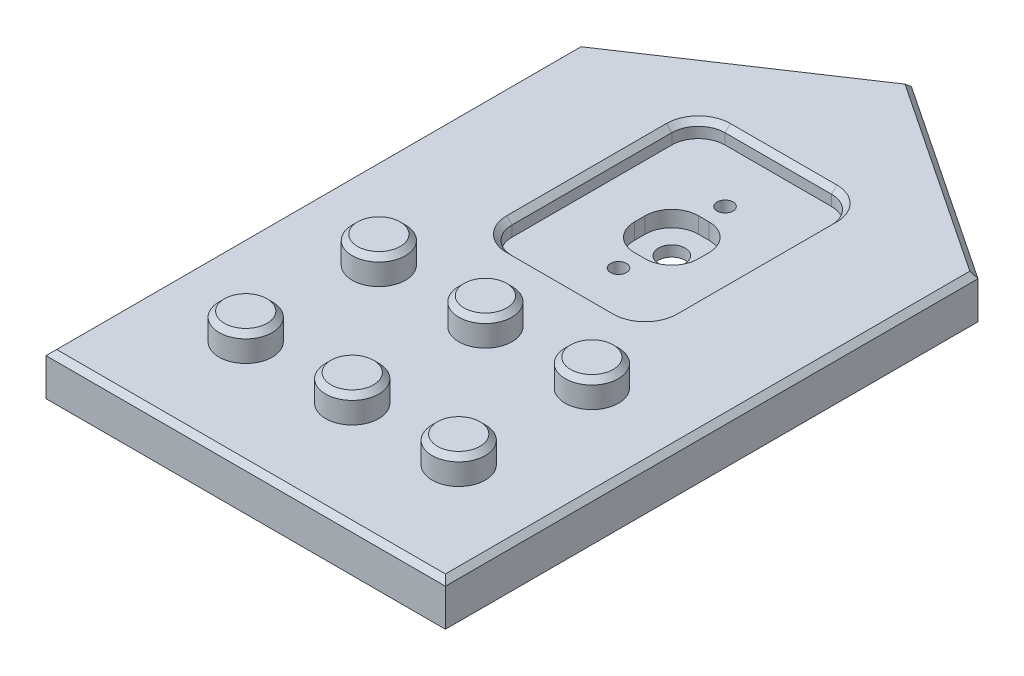
SolidWorks part; units mm, degrees
ref_plane "Front Plane" through (0, 0, 0) normal (0, 0, 1) x (1, 0, 0)
ref_plane "Top Plane" through (0, 0, 0) normal (0, 1, 0) x (1, 0, 0)
ref_plane "Right Plane" through (0, 0, 0) normal (1, 0, 0) x (0, 0, -1)
sketch "Sketch1" plane through (0, 0, 0) normal (0, 1, 0) x (1, 0, 0)
  line L0 (-37.5, 0) -> (37.5, 0)
  line L5 (37.5, 0) -> (37.5, 100)
  line L6 (37.5, 100) -> (-37.5, 100)
  line L7 (-37.5, 100) -> (-37.5, 0)
  line L8 (-37.5, 100) -> (0, 125)
  line L9 (0, 125) -> (37.5, 100)
  line L10 (0, 125) -> (0, 100) construction
  dimension "D1" = 100
  dimension "D2" = 75
  dimension "D3" = 25
extrude "Boss-Extrude1" add sketch "Sketch1" along normal blind 8
sketch "Sketch2" plane through (0, 0, 0) normal (1, 0, 0) x (0, 0, -1)
  line L0 (20, 8) -> (20, 34.3258) construction
  line L1 (0, 8) -> (100, 8) construction
  line L2 (15, 8) -> (23.3313, 8) construction
  line L3 (15, 8) -> (23.3313, 8)
  line L4 (0, 8) -> (0, 0) construction
  line L5 (20, 13) -> (20, 8)
  line L6 (20, 8) -> (15, 8)
  line L7 (15, 8) -> (15, 13)
  line L8 (15, 13) -> (20, 13)
  dimension "D2" = 20
revolve "Revolve1" add sketch "Sketch2" angle 360 about L0
pattern_linear "LPattern1" count 2 spacing 20 along (-1, 0, 0) count 2 spacing 20 along (1, 0, 0) of "Revolve1"
pattern_linear "LPattern2" count 2 spacing 25 along (0, 0, -1) of "LPattern1", "Revolve1"
sketch "Sketch3" plane through (0, 8, 0) normal (0, 1, 0) x (1, 0, 0)
  line L0 (0, 0) -> (0, 125) construction
  line L1 (-37.5, 0) -> (37.5, 0) construction
  line L3 (-15, 100) -> (15, 100)
  line L4 (-15, 100) -> (-15, 60)
  line L5 (-15, 60) -> (15, 60)
  line L6 (15, 100) -> (15, 60)
  point P9 (0, 60)
  point P10 (0, 0)
  dimension "D1" = 30
  dimension "D2" = 40
  dimension "D3" = 25
extrude "Cut-Extrude1" cut sketch "Sketch3" against normal blind 3
fillet "Fillet1" radius 5 4 edges at (15, 6.5, -60) (15, 6.5, -100) (-15, 6.5, -60) (-15, 6.5, -100)
sketch "Sketch4" plane through (0, 5, 0) normal (0, 1, 0) x (1, 0, 0)
  line L0 (0, 100) -> (0, 60) construction
  line L1 (10, 100) -> (-10, 100) construction
  line L2 (-10, 60) -> (10, 60) construction
  circle A0 centre (0, 90) radius 1.5
  circle A1 centre (0, 80) radius 2.5
  circle A2 centre (0, 70) radius 1.5
  point P6 (0, 90)
  point P7 (0, 80)
  point P8 (0, 70)
  dimension "D4" = 3
  dimension "D5" = 5
  dimension "D6" = 3
  dimension "D1" = 10
  dimension "D2" = 10
  dimension "D3" = 10
chamfer "Chamfer1" distance 1 angle 45 19 edges at (18.75, 8, -112.5) (-18.75, 8, -112.5) (0, 13, -25) (20, 13, -25) (-37.5, 8, -50) (-20, 13, -25) (0, 8, 0) (0, 13, -50) (20, 13, -50) (-20, 13, -50) (37.5, 8, -50) (15, 8, -80) (0, 8, -60) (0, 8, -100) (-15, 8, -80) (13.5355, 8, -61.4645) (13.5355, 8, -98.5355) (-13.5355, 8, -61.4645) (-13.5355, 8, -98.5355)
extrude "Cut-Extrude2" cut sketch "Sketch4" against normal through all
sketch "Sketch5" plane through (0, 5, 0) normal (0, 1, 0) x (1, 0, 0)
  line L0 (0, 100) -> (0, 60) construction
  line L1 (10, 100) -> (-10, 100) construction
  line L2 (-10, 60) -> (10, 60) construction
  line L4 (6, 74) -> (-6, 74)
  line L5 (6, 74) -> (6, 86)
  line L6 (6, 86) -> (-6, 86)
  line L7 (-6, 74) -> (-6, 86)
  line L8 (6, 74) -> (-6, 86) construction
  line L9 (6, 86) -> (-6, 74) construction
  point P6 (0, 80)
  dimension "D1" = 12
  dimension "D2" = 12
extrude "Cut-Extrude3" cut sketch "Sketch5" against normal blind 3
fillet "Fillet2" radius 5 4 edges at (6, 3.5, -74) (-6, 3.5, -74) (6, 3.5, -86) (-6, 3.5, -86)
